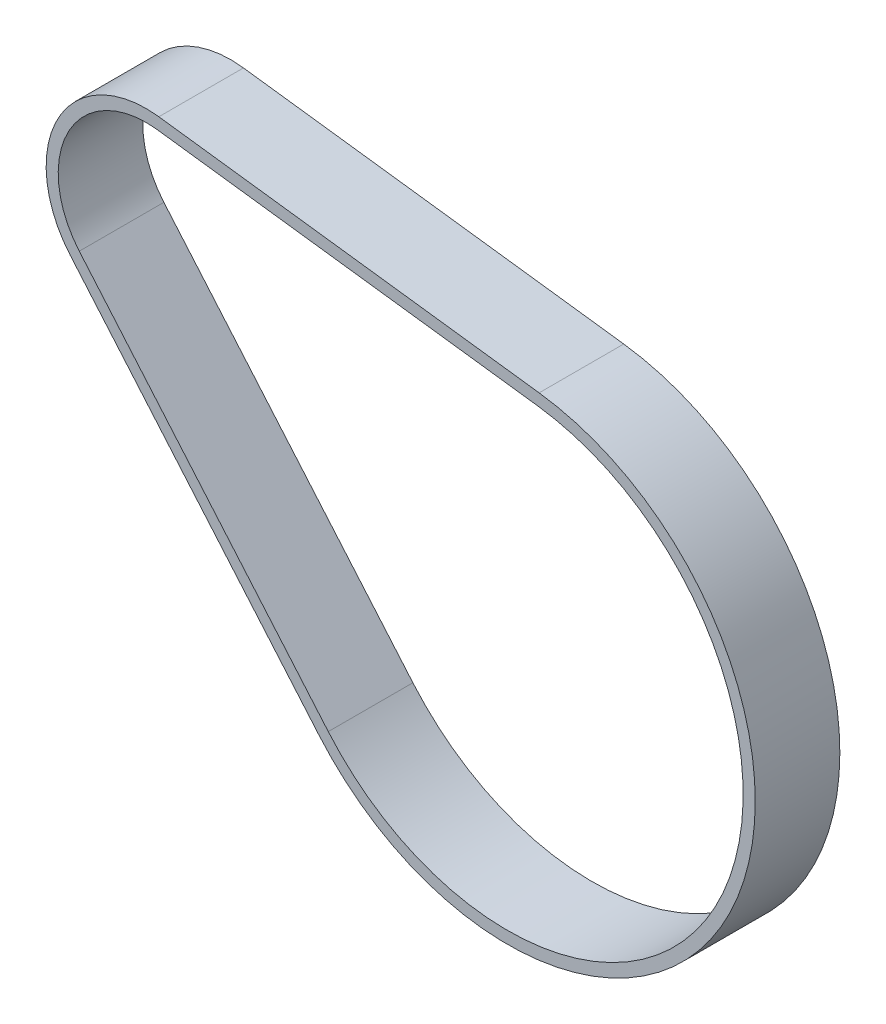
SolidWorks part; units mm, degrees
ref_plane "Front Plane" through (0, 0, 0) normal (0, 0, 1) x (1, 0, 0)
ref_plane "Top Plane" through (0, 0, 0) normal (0, 1, 0) x (1, 0, 0)
ref_plane "Right Plane" through (0, 0, 0) normal (1, 0, 0) x (0, 0, -1)
sketch "Sketch1" plane through (0, 0, 0) normal (0, 0, 1) x (1, 0, 0)
  line L0 (-28.8467, 24.3833) -> (2.6178, 20.3322)
  line L1 (-36.1914, 10.8101) -> (-15.5885, -13.3135)
  line L2 (-35.431, 11.4596) -> (-14.8281, -12.664)
  line L3 (-35.431, 11.4596) -> (-14.8281, -12.664)
  line L4 (-28.9744, 23.3915) -> (2.4901, 19.3404)
  arc A2 (18.0157, -7.4623) -> (2.4901, 19.3404) centre (0, 0) ccw
  arc A3 (18.9395, -7.845) -> (2.6178, 20.3322) centre (0, 0) ccw
  arc A4 (-8.7815, 17.4108) -> (18.0157, -7.4623) centre (0, 0) ccw construction
  arc A5 (-14.8281, -12.664) -> (18.0157, -7.4623) centre (0, 0) ccw
  arc A6 (-15.5885, -13.3135) -> (18.9395, -7.845) centre (0, 0) ccw
  arc A7 (18.9395, -7.845) -> (2.6178, 20.3322) centre (0, 0) ccw
  circle A8 centre (-29.9028, 16.181) radius 7.27 construction
  arc A9 (-28.9744, 23.3915) -> (-35.431, 11.4596) centre (-29.9028, 16.181) ccw
  arc A10 (-28.8467, 24.3833) -> (-36.1914, 10.8101) centre (-29.9028, 16.181) ccw
  circle A11 centre (-29.9028, 16.181) radius 8.27 construction
  arc A12 (-28.9744, 23.3915) -> (-35.431, 11.4596) centre (-29.9028, 16.181) ccw
  circle A13 centre (-29.9028, 16.181) radius 7.27 construction
  arc A14 (18.9395, -7.845) -> (-9.2318, 18.3037) centre (0, 0) ccw construction
  arc A16 (18.0157, -7.4623) -> (-8.7815, 17.4108) centre (0, 0) ccw construction
  point P2 (0, 0)
  dimension "D1" = 1
  dimension "D3" = 1
extrude "Boss-Extrude1" add sketch "Sketch1" against normal blind 7 contours L0 A10 L1 A6 A3 A9 L4 A2 A5 L2
